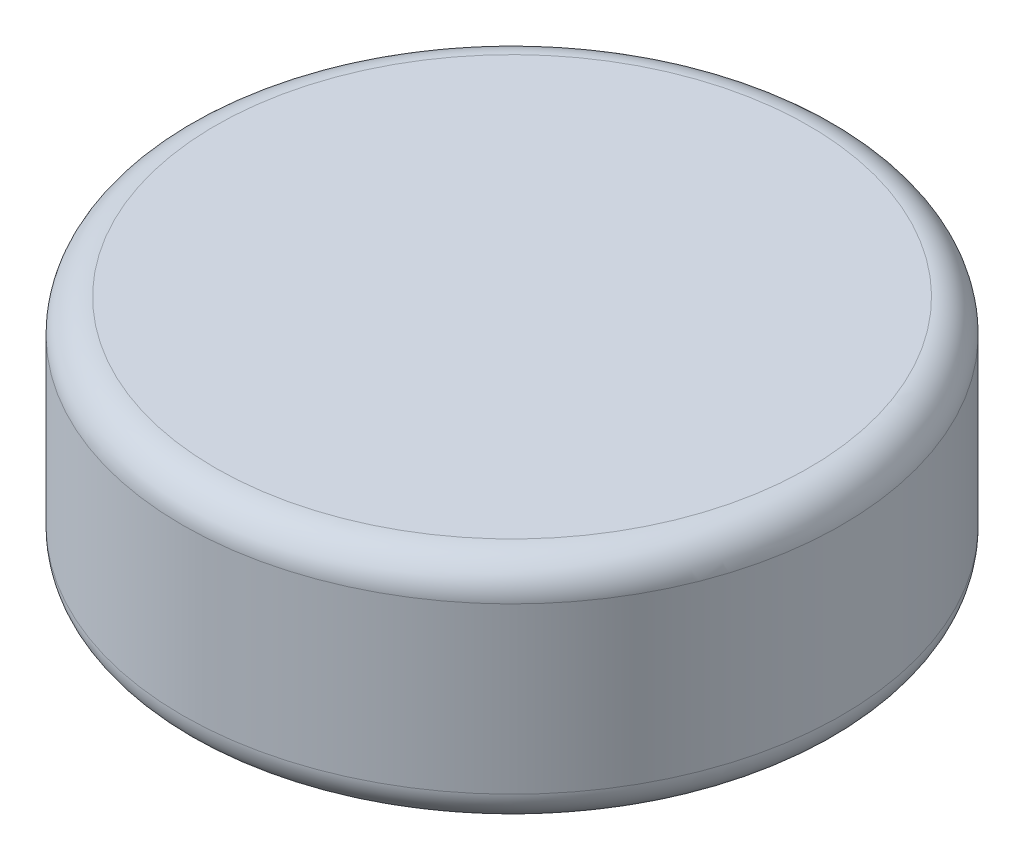
SolidWorks part; units mm, degrees
ref_plane "Front Plane" through (0, 0, 0) normal (0, 0, 1) x (1, 0, 0)
ref_plane "Top Plane" through (0, 0, 0) normal (0, 1, 0) x (1, 0, 0)
ref_plane "Right Plane" through (0, 0, 0) normal (1, 0, 0) x (0, 0, -1)
sketch "Sketch1" plane through (0, 0, 0) normal (0, 1, 0) x (1, 0, 0)
  circle A0 centre (0, 0) radius 5
extrude "Boss-Extrude1" add sketch "Sketch1" along normal blind 3.5
fillet "Fillet1" radius 0.5 2 edges at (0, 0, 5) (0, 3.5, 5)
